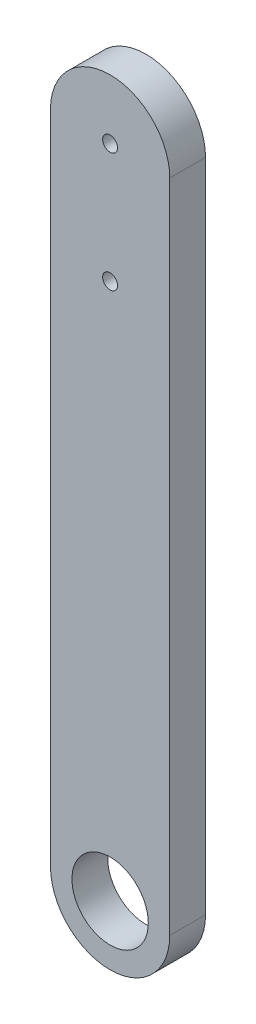
SolidWorks part; units mm, degrees
ref_plane "Plan de face" through (0, 0, 0) normal (0, 0, 1) x (1, 0, 0)
ref_plane "Plan de dessus" through (0, 0, 0) normal (0, 1, 0) x (1, 0, 0)
ref_plane "Plan de droite" through (0, 0, 0) normal (1, 0, 0) x (0, 0, -1)
sketch "Esquisse1" plane through (0, 0, 0) normal (0, 0, 1) x (1, 0, 0)
  line L3 (-69.1411, -13.7) -> (-69.1411, -33.7) construction
  line L4 (-79.1411, -13.7) -> (-79.1411, -123.7)
  line L5 (-59.1411, -123.7) -> (-59.1411, -13.7)
  line L6 (0, 0) -> (-129.4876, 0) construction
  line L7 (-129.4876, 0) -> (0, 0) construction
  line L8 (0, 0) -> (0, -104.4404) construction
  line L9 (-69.1411, -13.7) -> (-69.1411, -123.7) construction
  circle A2 centre (-69.1411, -13.7) radius 1.25
  circle A5 centre (-69.1411, -33.7) radius 1.25
  arc A10 (-79.1411, -123.7) -> (-59.1411, -123.7) centre (-69.1411, -123.7) ccw
  arc A11 (-59.1411, -13.7) -> (-79.1411, -13.7) centre (-69.1411, -13.7) ccw
  circle A12 centre (-69.1411, -123.7) radius 6.4
  dimension "D3" = 12.8
  dimension "D5" = 2.5
  dimension "D6" = 13.7
  dimension "D7" = 110
  dimension "D8" = 2.5
  dimension "D1" = 20
  dimension "D2" = 20
  dimension "D4" = 59.1411
extrude "Boss.-Extru.1" add sketch "Esquisse1" along normal blind 6
